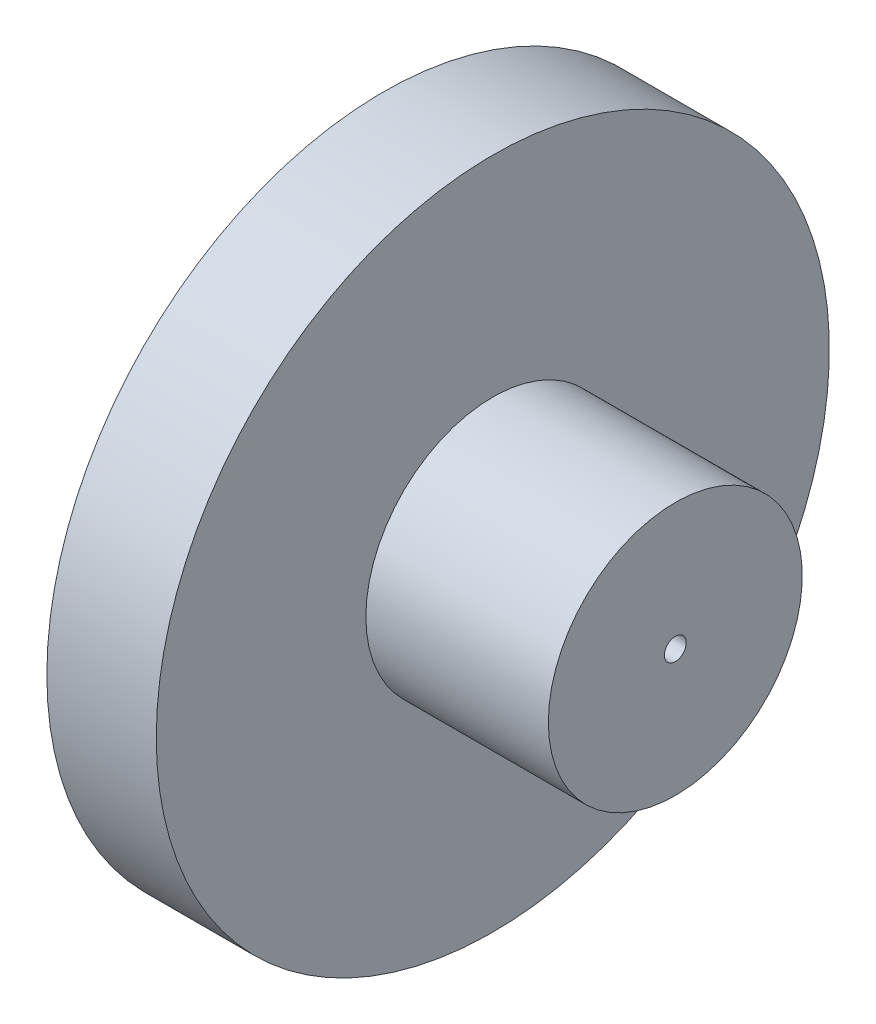
SolidWorks part; units mm, degrees
ref_plane "Front Plane" through (0, 0, 0) normal (0, 0, 1) x (1, 0, 0)
ref_plane "Top Plane" through (0, 0, 0) normal (0, 1, 0) x (1, 0, 0)
ref_plane "Right Plane" through (0, 0, 0) normal (1, 0, 0) x (0, 0, -1)
sketch "Sketch1" plane through (0, 0, 0) normal (0, 0, 1) x (1, 0, 0)
  line L0 (-106, 5) -> (-106, 32.8101)
  line L1 (-106, 32.8101) -> (-27.4077, 32.8101)
  line L2 (-27.4077, 32.8101) -> (-27.4077, 153.8101)
  line L3 (-27.4077, 153.8101) -> (22.5923, 153.8101)
  line L4 (22.5923, 153.8101) -> (22.5923, 58.0228)
  line L5 (22.5923, 58.0228) -> (106, 58.0228)
  line L6 (106, 58.0228) -> (106, 5)
  line L7 (106, 5) -> (-106, 5)
  line L8 (-37.412, 0) -> (19.8786, 0) construction
  point P10 (0, 5)
  dimension "D1" = 121
  dimension "D2" = 212
  dimension "D3" = 50
  dimension "D4" = 5
revolve "Revolve1" add sketch "Sketch1" angle 360 about L8
